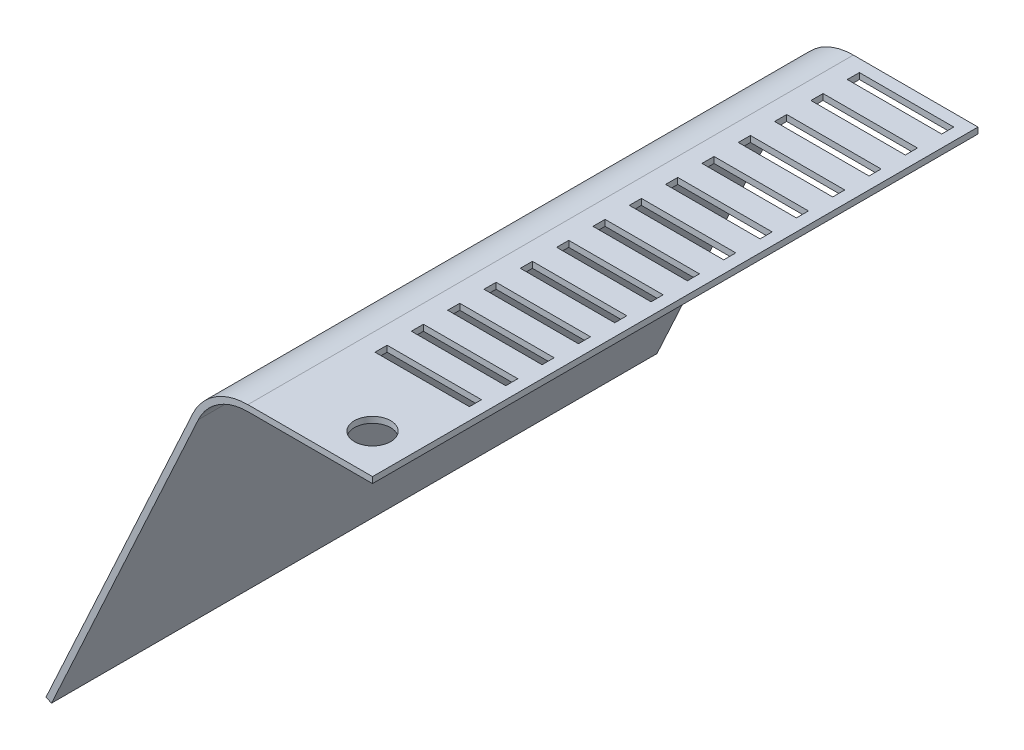
SolidWorks part; units mm, degrees
ref_plane "Front Plane" through (0, 0, 0) normal (0, 0, 1) x (1, 0, 0)
ref_plane "Top Plane" through (0, 0, 0) normal (0, 1, 0) x (1, 0, 0)
ref_plane "Right Plane" through (0, 0, 0) normal (1, 0, 0) x (0, 0, -1)
sketch "Sketch1" plane through (0, 0, 0) normal (0, 0, 1) x (1, 0, 0)
  line L0 (0, 0) -> (-205.92, 0)
  line L1 (-296.7562, -58.1816) -> (-539.303, -585.0317)
  arc A0 (-296.7562, -58.1816) -> (-205.92, 0) centre (-205.92, -100) cw
  dimension "D1" = 100
  dimension "D2" = 205.92
  dimension "D3" = 114.72
  dimension "D4" = 580
extrude "Extrude-Thin1" add sketch "Sketch1" along normal mid plane 1000 thin thin type one direction reverse wall 10
sketch "Sketch3" plane through (0, 0, 0) normal (0, 1, 0) x (1, 0, 0)
  line L0 (0, 500) -> (-205.92, 500) construction
  line L1 (-175.92, 460) -> (-20, 460)
  line L2 (-175.92, 460) -> (-175.92, 480)
  line L3 (-175.92, 480) -> (-20, 480)
  line L4 (-20, 460) -> (-20, 480)
  line L5 (-175.92, 460) -> (-20, 480) construction
  line L6 (-175.92, 480) -> (-20, 460) construction
  line L7 (0, -500) -> (0, 500) construction
  line L8 (-205.92, -500) -> (-205.92, 500) construction
  point P0 (-97.96, 470)
  dimension "D1" = 20
  dimension "D2" = 20
  dimension "D3" = 20
  dimension "D4" = 30
extrude "Cut-Extrude1" cut sketch "Sketch3" against normal mid plane 452
pattern_linear "LPattern1" count 14 spacing 60 along (0, 0, 1) of "Cut-Extrude1"
sketch "Sketch4" plane through (0, 0, 0) normal (0, 1, 0) x (1, 0, 0)
  line L0 (0, -500) -> (-205.92, -500) construction
  line L1 (0, -500) -> (0, 500) construction
  circle A0 centre (-65, -435) radius 30
  dimension "D3" = 60
  dimension "D1" = 65
  dimension "D2" = 65
extrude "Cut-Extrude2" cut sketch "Sketch4" against normal mid plane 452
